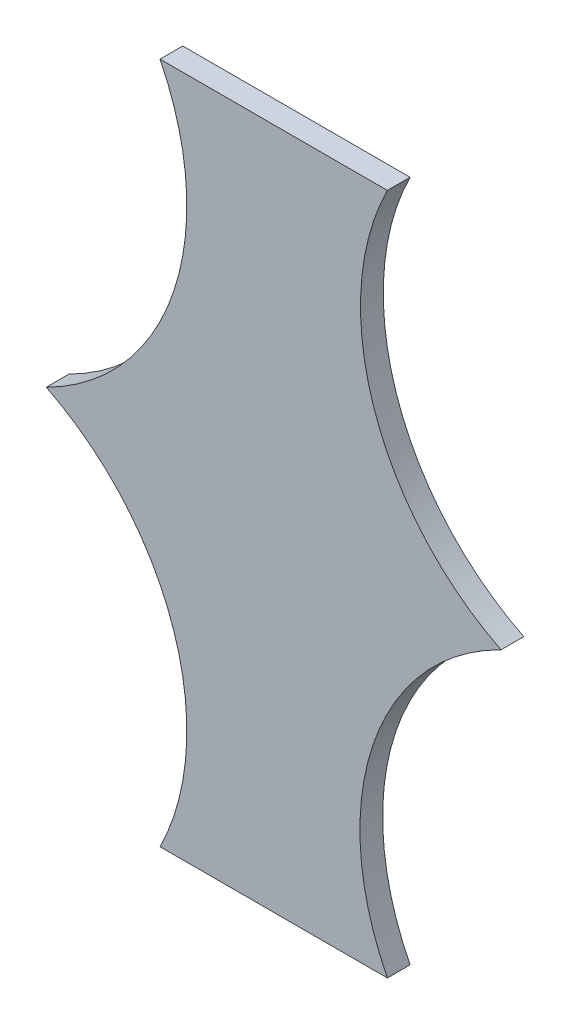
SolidWorks part; units mm, degrees
ref_plane "Front Plane" through (0, 0, 0) normal (1, 0, 0) x (0, 1, 0)
ref_plane "Top Plane" through (0, 0, 0) normal (0, 0, 1) x (0, 1, 0)
ref_plane "Right Plane" through (0, 0, 0) normal (0, 1, 0) x (-1, 0, 0)
sketch "Sketch1" plane through (0, 0, 0) normal (0, 0, 1) x (0, 1, 0)
  line L5 (-499.9648, 99.9428) -> (-499.9648, 299.9149)
  line L8 (99.9648, 99.9648) -> (99.9648, 299.9149)
  arc A0 (99.9648, 299.9149) -> (-200, 400) centre (0.0249, 499.9398) cw
  arc A1 (-200, 400) -> (-499.9648, 299.9149) centre (-400.0249, 499.9398) cw
  arc A2 (-499.9648, 99.9428) -> (-200, 0) centre (-399.2355, -97.855) cw
  arc A3 (-200, 0) -> (99.9648, 99.9648) centre (-0.0352, -100) cw
  point P16 (0, 0)
  point P17 (-499.7298, 99.9648)
extrude "Boss-Extrude3" add sketch "Sketch1" along normal blind 20 contours L5 A1 A0 L8 A3 A2
